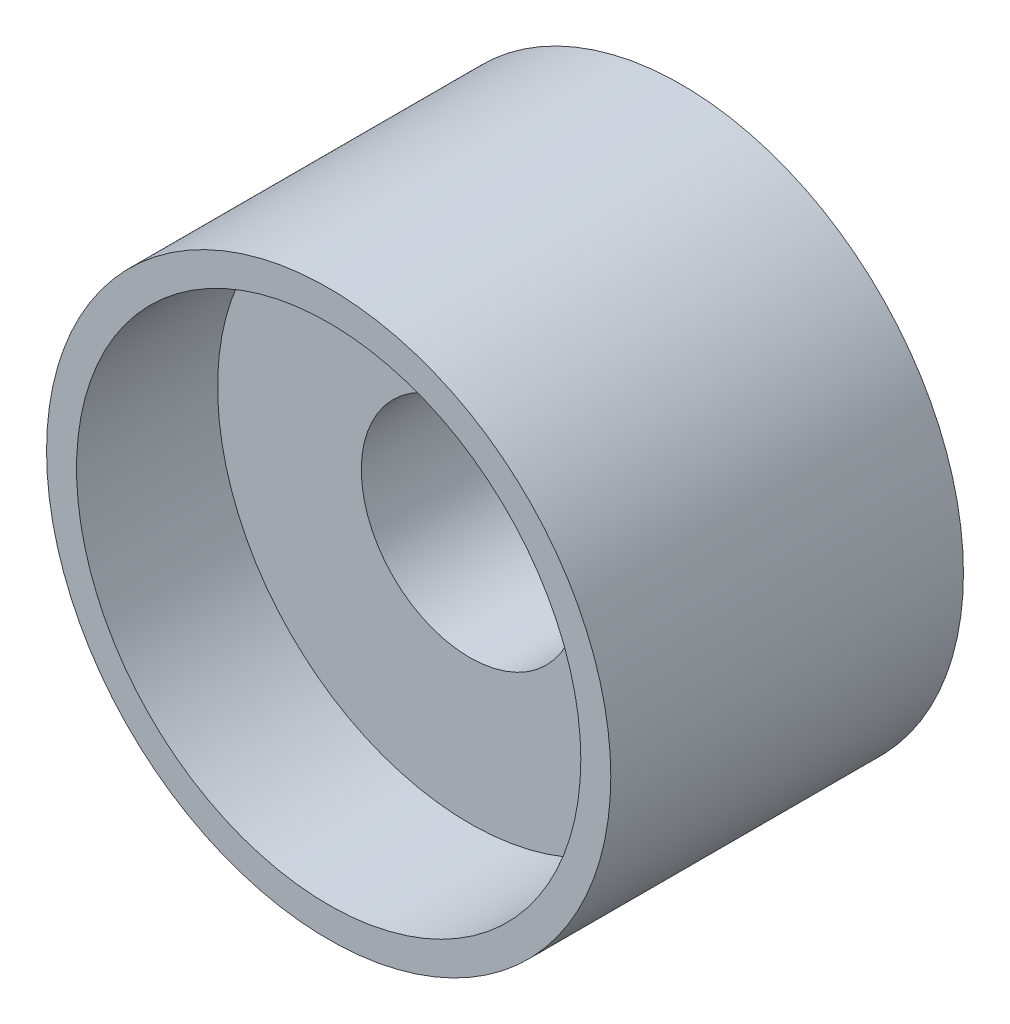
SolidWorks part; units mm, degrees
ref_plane "Front Plane" through (0, 0, 0) normal (0, 0, 1) x (1, 0, 0)
ref_plane "Top Plane" through (0, 0, 0) normal (0, 1, 0) x (1, 0, 0)
ref_plane "Right Plane" through (0, 0, 0) normal (1, 0, 0) x (0, 0, -1)
sketch "Sketch1" plane through (0, 0, 0) normal (0, 0, 1) x (1, 0, 0)
  circle A0 centre (0, 0) radius 16
  circle A1 centre (0, 0) radius 6.15
  dimension "D1" = 32
  dimension "D2" = 12.3
extrude "Boss-Extrude1" add sketch "Sketch1" along normal blind 20
sketch "Sketch2" plane through (0, 0, 20) normal (0, 0, 1) x (1, 0, 0)
  circle A0 centre (0, 0) radius 14.3
  circle A1 centre (0, 0) radius 16 construction
  dimension "D1" = 1.7
extrude "Cut-Extrude1" cut sketch "Sketch2" against normal blind 8
